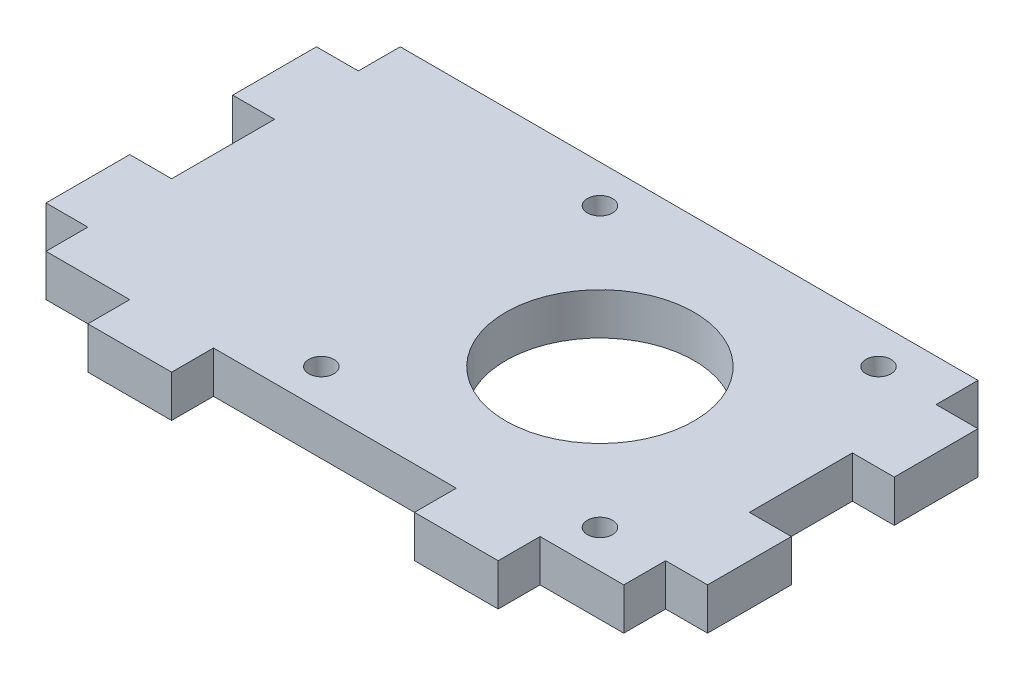
SolidWorks part; units mm, degrees
ref_plane "前视基准面" through (0, 0, 0) normal (0, 0, 1) x (1, 0, 0)
ref_plane "上视基准面" through (0, 0, 0) normal (0, 1, 0) x (1, 0, 0)
ref_plane "右视基准面" through (0, 0, 0) normal (1, 0, 0) x (0, 0, -1)
sketch "草图1" plane through (0, 0, 0) normal (0, 1, 0) x (1, 0, 0)
  line L0 (10.5, 31.613) -> (10.5, -35.7576) construction
  line L1 (-34.5, 21.15) -> (34.5, 21.15)
  line L2 (-34.5, 21.15) -> (-34.5, 16.15)
  line L3 (-34.5, -21.15) -> (-24.5, -21.15)
  line L4 (34.5, 21.15) -> (34.5, 16.15)
  line L5 (-34.5, 21.15) -> (34.5, -21.15) construction
  line L6 (-34.5, -21.15) -> (34.5, 21.15) construction
  line L7 (55.8148, 0) -> (-49.3871, 0) construction
  line L8 (-40.8362, 26.15) -> (62.1632, 26.15) construction
  line L9 (-24.5, 35.1111) -> (-24.5, -38.7375) construction
  line L10 (46.6161, -26.15) -> (-44.4639, -26.15) construction
  line L11 (24.5, 33.0382) -> (24.5, -42.3651) construction
  line L12 (-39.5, 36.2772) -> (-39.5, -43.4016) construction
  line L13 (39.5, 33.9519) -> (39.5, -46.2519) construction
  line L14 (-49.3871, -16.15) -> (50.6324, -16.15) construction
  line L15 (46.6161, 16.15) -> (-44.4639, 16.15) construction
  line L16 (-34.5, 6.15) -> (-34.5, -6.15)
  line L17 (-6.1348, 16.6348) -> (27.1348, 16.6348) construction
  line L18 (-6.1348, 16.6348) -> (-6.1348, -16.6348) construction
  line L19 (-6.1348, -16.6348) -> (27.1348, -16.6348) construction
  line L20 (27.1348, 16.6348) -> (27.1348, -16.6348) construction
  line L21 (-6.1348, 16.6348) -> (27.1348, -16.6348) construction
  line L22 (-6.1348, -16.6348) -> (27.1348, 16.6348) construction
  line L23 (24.5, -21.15) -> (34.5, -21.15)
  line L24 (-24.5, -21.15) -> (-24.5, -26.15)
  line L25 (-24.5, -26.15) -> (-14.5, -26.15)
  line L26 (-14.5, -21.15) -> (-14.5, -26.15)
  line L27 (34.5, -16.15) -> (34.5, -21.15)
  line L28 (24.5, -21.15) -> (24.5, -26.15)
  line L29 (24.5, -26.15) -> (14.5, -26.15)
  line L30 (14.5, -21.15) -> (14.5, -26.15)
  line L31 (-34.5, 16.15) -> (-39.5, 16.15)
  line L32 (-34.5, -16.15) -> (-34.5, -21.15)
  line L33 (-34.5, 6.15) -> (-39.5, 6.15)
  line L34 (-39.5, 16.15) -> (-39.5, 6.15)
  line L35 (-34.5, -16.15) -> (-39.5, -16.15)
  line L36 (-14.5, -21.15) -> (14.5, -21.15)
  line L37 (-34.5, -6.15) -> (-39.5, -6.15)
  line L38 (-39.5, -16.15) -> (-39.5, -6.15)
  line L39 (34.5, -16.15) -> (39.5, -16.15)
  line L40 (34.5, 6.15) -> (34.5, -6.15)
  line L41 (34.5, -6.15) -> (39.5, -6.15)
  line L42 (39.5, -16.15) -> (39.5, -6.15)
  line L43 (34.5, 16.15) -> (39.5, 16.15)
  line L45 (34.5, 6.15) -> (39.5, 6.15)
  line L46 (39.5, 16.15) -> (39.5, 6.15)
  circle A0 centre (10.5, 0) radius 11.25
  circle A1 centre (-6.1348, 16.6348) radius 1.5
  circle A2 centre (27.1348, 16.6348) radius 1.5
  circle A3 centre (-6.1348, -16.6348) radius 1.5
  circle A4 centre (27.1348, -16.6348) radius 1.5
  point P0 (0, 0)
  point P60 (0, 0)
  dimension "D13" = 10
  dimension "D1" = 69
  dimension "D2" = 42.3
  dimension "D3" = 21.15
  dimension "D4" = 24
  dimension "D5" = 10
  dimension "D6" = 5
  dimension "D7" = 10
  dimension "D8" = 5
  dimension "D9" = 5
  dimension "D10" = 5
  dimension "D11" = 5
  dimension "D12" = 5
extrude "凸台-拉伸1" add sketch "草图1" along normal blind 5
